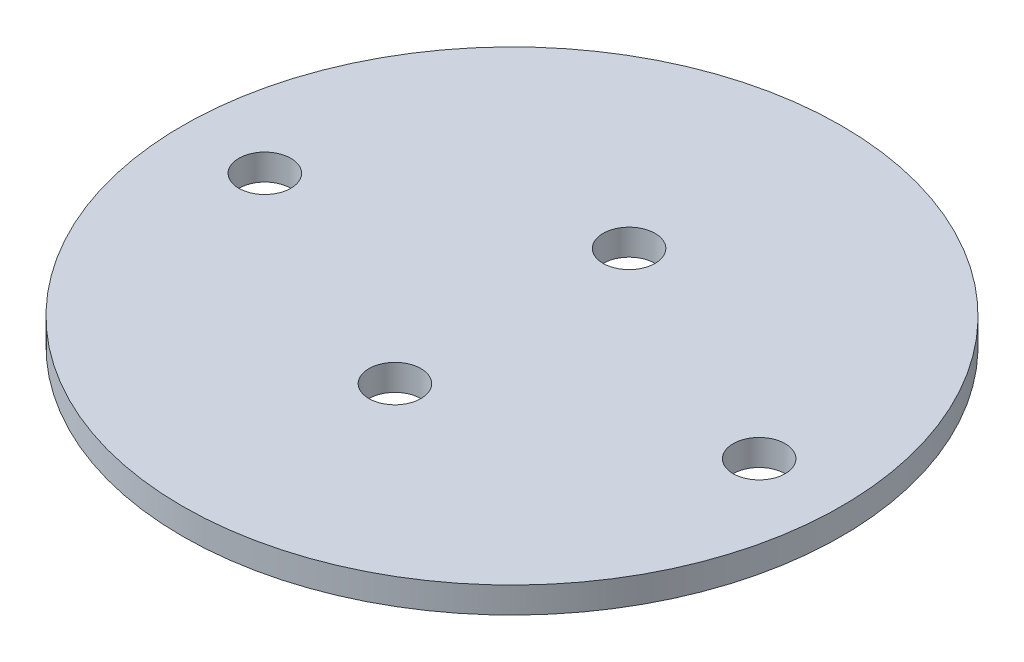
SolidWorks part; units mm, degrees
ref_plane "Front Plane" through (0, 0, 0) normal (0, 0, 1) x (1, 0, 0)
ref_plane "Top Plane" through (0, 0, 0) normal (0, 1, 0) x (1, 0, 0)
ref_plane "Right Plane" through (0, 0, 0) normal (1, 0, 0) x (0, 0, -1)
sketch "Sketch1" plane through (0, 0, 0) normal (0, 1, 0) x (1, 0, 0)
  line L0 (-28.5, 0) -> (28.5, 0) construction
  line L1 (0, 0) -> (0, 13.5)
  line L2 (0, 0) -> (0, -13.5)
  circle A0 centre (0, 0) radius 38
  circle A1 centre (28.5, 0) radius 3
  circle A2 centre (-28.5, 0) radius 3
  circle A3 centre (0, 13.5) radius 3
  circle A4 centre (0, -13.5) radius 3
  circle A5 centre (-28.5, 0) radius 6.25 construction
  circle A6 centre (0, 13.5) radius 12.5 construction
  circle A7 centre (0, -13.5) radius 12.5 construction
  circle A8 centre (28.5, 0) radius 6.25 construction
  point P2 (0, 0)
  point P11 (0, 0)
  dimension "D1" = 76
  dimension "D3" = 6
  dimension "D4" = 13.5
  dimension "D5" = 6
  dimension "D6" = 12.5
  dimension "D7" = 25
  dimension "D2" = 57
extrude "Boss-Extrude1" add sketch "Sketch1" against normal blind 3
